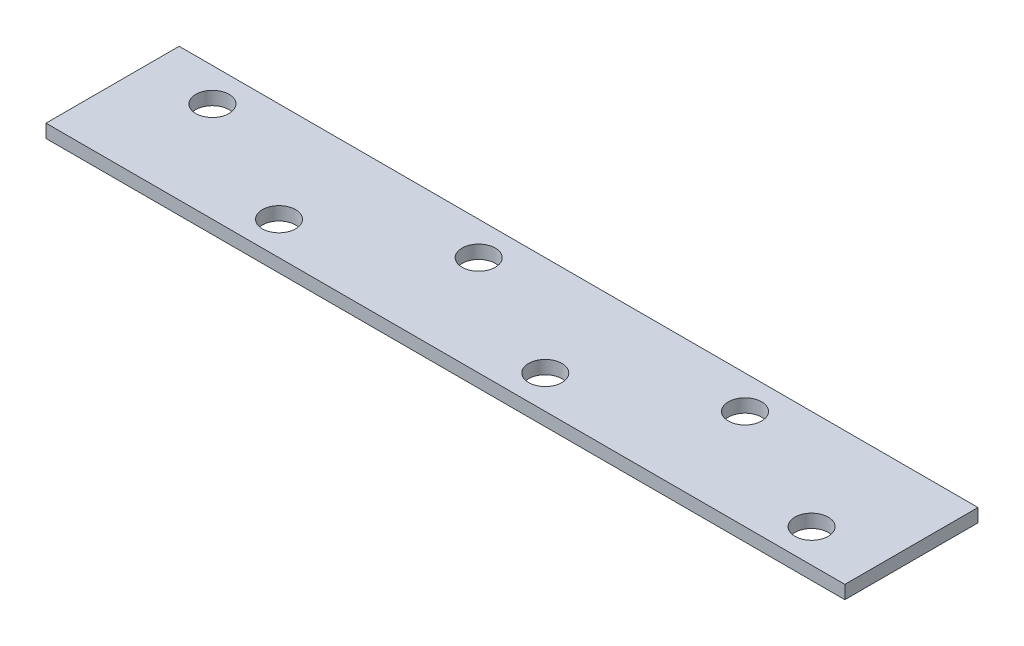
SolidWorks part; units mm, degrees
ref_plane "Спереди" through (0, 0, 0) normal (0, 0, 1) x (1, 0, 0)
ref_plane "Сверху" through (0, 0, 0) normal (0, 1, 0) x (1, 0, 0)
ref_plane "Справа" through (0, 0, 0) normal (1, 0, 0) x (0, 0, -1)
sketch "Эскиз2" plane through (0, 0, 0) normal (0, 1, 0) x (1, 0, 0)
  line L1 (-60, 10) -> (60, 10)
  line L2 (-60, 10) -> (-60, -10)
  line L3 (-60, -10) -> (60, -10)
  line L4 (60, 10) -> (60, -10)
  line L5 (-60, 10) -> (60, -10) construction
  line L6 (-60, -10) -> (60, 10) construction
  circle A0 centre (-50, 5) radius 2.5
  circle A1 centre (-30, 5) radius 2.5 construction
  circle A2 centre (-10, 5) radius 2.5
  circle A3 centre (10, 5) radius 2.5 construction
  circle A4 centre (30, 5) radius 2.5
  circle A5 centre (50, 5) radius 2.5 construction
  circle A6 centre (-30, -5) radius 2.5
  circle A7 centre (-10, -5) radius 2.5 construction
  circle A8 centre (10, -5) radius 2.5
  circle A9 centre (30, -5) radius 2.5 construction
  circle A10 centre (50, -5) radius 2.5
  circle A11 centre (-50, -5) radius 2.5 construction
  point P0 (0, 0)
  dimension "D3" = 5
  dimension "D1" = 20
  dimension "D2" = 120
  dimension "D4" = 5
  dimension "D5" = 10
  dimension "D9" = 5
  dimension "D8" = 40
  dimension "D6" = 6
  dimension "D7" = 2
extrude "Бобышка-Вытянуть1" add sketch "Эскиз2" along normal blind 2
equation "\"print_offset\"= 0.5"
equation "\"tape_width\"=51"
equation "\"tape_thikness\"=5"
equation "\"tape_distance\"=5"
equation "\"screw_d\"=3"
equation "\"screw_hh_d\"=5.3"
equation "\"nut_d\"=5.5"
equation "\"nut_h\"=2.5"
equation "\"sitting_screws\"=30"
equation "\"mount_size\"=42"
equation "\"hip_to_tube\" = 65"
equation "\"back_to_tube\"= 60"
equation "\"tube_d\"= 16"
equation "\"bearing_d1\"= 20"
equation "\"bearing_d2\"= 42"
equation "\"bearing_h\"= 12"
equation "\"tube_A\"= 250"
equation "\"tube_B\"= 384"
equation "\"tube_C\"= 300"
equation "\"tube_thikness\"=1"
equation "\"tube_bend_radius\"= 80"
equation "\"plate_a\"= 20"
equation "\"plate_b\"= 120"
equation "\"plate_holes\"= 5"
equation "\"plate_holes_a\"= ( 2.5 + 7.5 ) / 2"
equation "\"plate_holes_b\"= ( 7.5 + 12.5 ) / 2"
equation "\"plate_holes_step\"= 40"
equation "\"D1@Эскиз2\"=\"plate_a\""
equation "\"D2@Эскиз2\"=\"plate_b\""
equation "\"D3@Эскиз2\"=\"plate_holes\""
equation "\"D4@Эскиз2\"=\"plate_holes\""
equation "\"D9@Эскиз2\"=\"D4@Эскиз2\""
equation "\"D5@Эскиз2\"=\"plate_holes_b\""
equation "\"D8@Эскиз2\"=\"plate_holes_step\""
